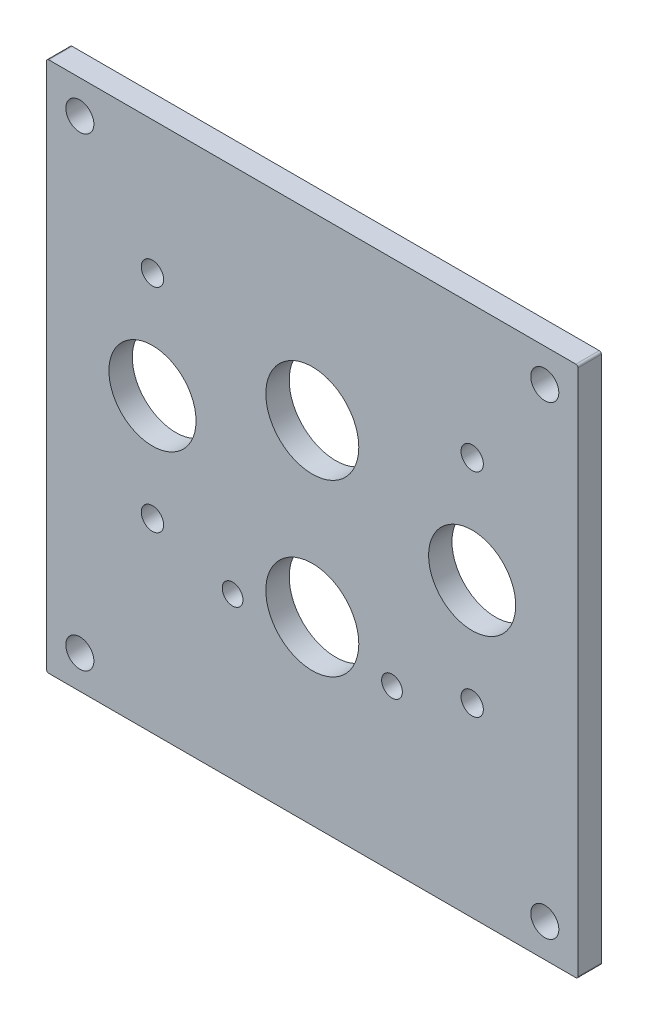
SolidWorks part; units mm, degrees
material "6061 Alloy"
ref_plane "Front" through (0, 0, 0) normal (0, 0, 1) x (1, 0, 0)
ref_plane "Top" through (0, 0, 0) normal (0, 1, 0) x (1, 0, 0)
ref_plane "Right" through (0, 0, 0) normal (1, 0, 0) x (0, 0, -1)
sketch "Sketch1" plane through (0, 0, 0) normal (0, 0, 1) x (1, 0, 0)
  line L2 (-63.5, -63.5) -> (0, -63.5)
  line L3 (0, 63.5) -> (0, -63.5)
  line L9 (-63.5, 63.5) -> (-63.5, -63.5)
  line L10 (0, 63.5) -> (-63.5, 63.5)
  dimension "D1" = 63.5
  dimension "D2" = 127
extrude "Extrude1" add sketch "Sketch1" along normal mid plane 5.59
sketch "Sketch2" plane through (0, 0, 2.795) normal (0, 0, 1) x (1, 0, 0)
  line L0 (0, 63.5) -> (0, -63.5) construction
  line L1 (-63.5, 63.5) -> (-63.5, -63.5) construction
  line L2 (0, 63.5) -> (-63.5, 63.5) construction
  line L3 (0, 0) -> (-63.5, 0) construction
  line L4 (0, 0) -> (0, 97.0716) construction
  circle A0 centre (-55.5625, 55.5625) radius 3.3528
  circle A1 centre (-38.2016, 6.35) radius 10.414
  circle A2 centre (-38.2083, -19.05) radius 2.667
  circle A3 centre (-19.05, -25.1079) radius 2.4765
  circle A4 centre (-38.2083, 31.75) radius 2.667
  circle A5 centre (0, -20.3454) radius 11.1125
  circle A6 centre (-55.5625, -55.5625) radius 3.3528
  circle A8 centre (0, 20.3454) radius 11.1125
  point P1 (0, 0)
  dimension "D2" = 22.225
  dimension "D5" = 6.7056
  dimension "D6" = 20.828
  dimension "D9" = 4.953
  dimension "D10" = 5.334
  dimension "D11" = 38.1
  dimension "D1" = 20.3454
  dimension "D3" = 7.9375
  dimension "D4" = 7.9375
  dimension "D7" = 38.2016
  dimension "D8" = 6.35
  dimension "D12" = 25.1079
  dimension "D13" = 19.05
  dimension "D14" = 38.2083
  dimension "D15" = 31.75
extrude "Extrude2" cut sketch "Sketch2" against normal through all
fillet "Fillet1" radius 0.508 2 edges at (-63.5, -63.5, 0) (-63.5, 63.5, 0)
mirror "Mirror1" about plane through (0, -110.584, 2.795) normal (1, 0, 0) of bodies 104
